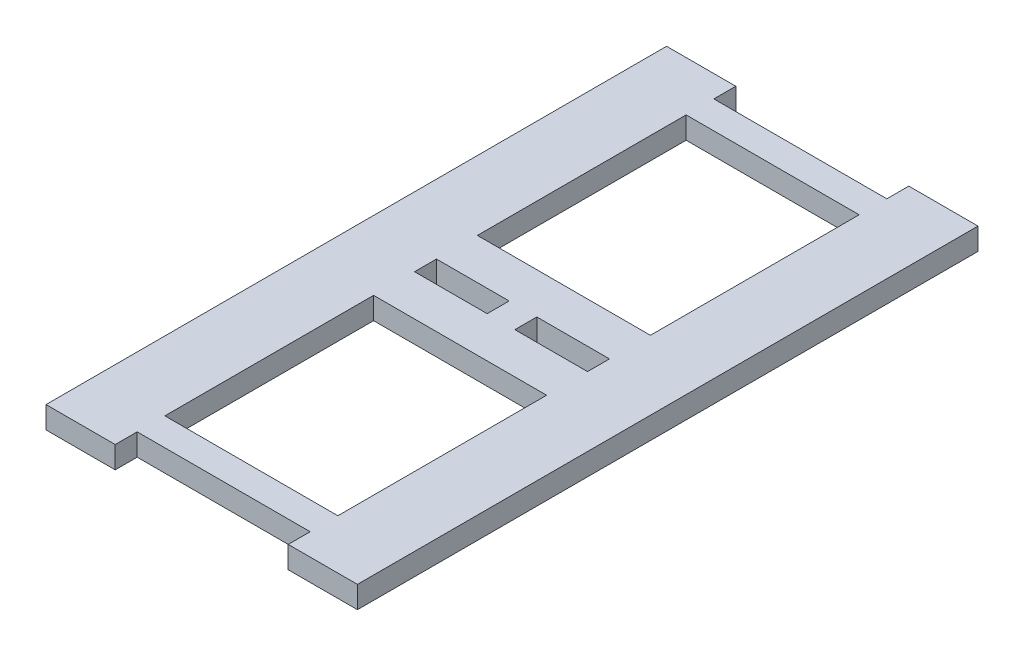
SolidWorks part; units mm, degrees
material "Mahogany"
ref_plane "Front Plane" through (0, 0, 0) normal (0, 0, 1) x (1, 0, 0)
ref_plane "Top Plane" through (0, 0, 0) normal (0, 1, 0) x (1, 0, 0)
ref_plane "Right Plane" through (0, 0, 0) normal (1, 0, 0) x (0, 0, -1)
sketch "Sketch1" plane through (0, 0, 0) normal (0, 0, 1) x (1, 0, 0)
  line L0 (-27.5, 19.2) -> (-27.5, 22.375) construction
  line L1 (-17.5, 22.375) -> (-17.5, 19.2) construction
  line L2 (-17.5, 19.2) -> (-27.5, 19.2) construction
  line L3 (-27.5, 22.375) -> (-17.5, 22.375) construction
  line L4 (-52.5, 22.375) -> (-52.5, 19.2) construction
  line L5 (-52.5, 19.2) -> (-62.5, 19.2) construction
  line L6 (-62.5, 22.375) -> (-52.5, 22.375) construction
  line L7 (-62.5, 19.2) -> (-62.5, 22.375) construction
  line L8 (-17.5, 19.2) -> (-27.5, 19.2)
  line L9 (-17.5, 22.375) -> (-17.5, 19.2)
  line L10 (-27.5, 22.375) -> (-17.5, 22.375)
  line L11 (-27.5, 19.2) -> (-27.5, 22.375)
  line L12 (-62.5, 19.2) -> (-62.5, 22.375)
  line L13 (-62.5, 22.375) -> (-52.5, 22.375)
  line L14 (-52.5, 22.375) -> (-52.5, 19.2)
  line L15 (-52.5, 19.2) -> (-62.5, 19.2)
extrude "Boss-Extrude1" add sketch "Sketch1" against normal up to surface (89.675 mm away)
sketch "Sketch2" plane through (0, 22.375, 0) normal (0, 1, 0) x (1, 0, 0)
  line L0 (-27.5, 86.5) -> (-52.5, 86.5)
  line L1 (-52.5, 86.5) -> (-52.5, 82.5)
  line L2 (-52.5, 89.675) -> (-52.5, 0) construction
  line L3 (-52.5, 82.5) -> (-27.5, 82.5)
  line L4 (-27.5, 89.675) -> (-27.5, 0) construction
  line L5 (-27.5, 82.5) -> (-27.5, 86.5)
  line L6 (-17.5, 44.8375) -> (-62.5, 44.8375) construction
  line L7 (-17.5, 89.675) -> (-17.5, 0) construction
  line L8 (-62.5, 89.675) -> (-62.5, 0) construction
  line L9 (-27.5, 7.175) -> (-27.5, 3.175)
  line L10 (-52.5, 7.175) -> (-27.5, 7.175)
  line L11 (-52.5, 3.175) -> (-52.5, 7.175)
  line L12 (-27.5, 3.175) -> (-52.5, 3.175)
  line L14 (-52.5, 37.3375) -> (-27.5, 37.3375)
  line L15 (-52.5, 37.3375) -> (-52.5, 52.3375)
  line L16 (-52.5, 52.3375) -> (-27.5, 52.3375)
  line L17 (-27.5, 37.3375) -> (-27.5, 52.3375)
  line L18 (-52.5, 37.3375) -> (-27.5, 52.3375) construction
  line L19 (-52.5, 52.3375) -> (-27.5, 37.3375) construction
  point P13 (-52.5, 44.8375)
  point P21 (-40, 44.8375)
  dimension "D1" = 4
  dimension "D2" = 15
extrude "Boss-Extrude2" add sketch "Sketch2" against normal up to surface (3.175 mm away) up to face at (-57.5, 19.2, -44.8375)
sketch "Sketch3" plane through (0, 22.375, 0) normal (0, 1, 0) x (1, 0, 0)
  line L0 (-17.5, 44.8375) -> (-62.5, 44.8375) construction
  line L1 (-40, 52.3375) -> (-40, 37.3375) construction
  line L2 (-52.5, 37.3375) -> (-52.5, 7.175) construction
  line L3 (-27.5, 7.175) -> (-52.5, 7.175) construction
  line L4 (-27.5, 37.3375) -> (-27.5, 7.175) construction
  line L5 (-52.5, 37.3375) -> (-27.5, 37.3375) construction
  line L6 (-27.5, 52.3375) -> (-52.5, 52.3375) construction
  line L7 (-52.5, 82.5) -> (-52.5, 52.3375) construction
  line L8 (-52.5, 82.5) -> (-27.5, 82.5) construction
  line L9 (-27.5, 82.5) -> (-27.5, 52.3375) construction
  line L10 (-52.5, 37.3375) -> (-52.5, 7.175) construction
  line L11 (-27.5, 7.175) -> (-52.5, 7.175) construction
  line L12 (-27.5, 37.3375) -> (-27.5, 7.175) construction
  line L13 (-52.5, 37.3375) -> (-27.5, 37.3375) construction
  line L14 (-17.5, 89.675) -> (-27.5, 89.675)
  line L15 (-27.5, 89.675) -> (-27.5, 86.5)
  line L16 (-27.5, 86.5) -> (-52.5, 86.5)
  line L17 (-52.5, 86.5) -> (-52.5, 89.675)
  line L18 (-52.5, 89.675) -> (-62.5, 89.675)
  line L19 (-62.5, 89.675) -> (-62.5, 0)
  line L20 (-62.5, 0) -> (-52.5, 0)
  line L21 (-52.5, 0) -> (-52.5, 3.175)
  line L22 (-52.5, 3.175) -> (-27.5, 3.175)
  line L23 (-27.5, 3.175) -> (-27.5, 0)
  line L24 (-27.5, 0) -> (-17.5, 0)
  line L25 (-17.5, 0) -> (-17.5, 89.675)
  line L26 (-17.5, 89.675) -> (-27.5, 89.675) construction
  line L27 (-27.5, 89.675) -> (-27.5, 86.5) construction
  line L28 (-27.5, 86.5) -> (-52.5, 86.5) construction
  line L29 (-52.5, 86.5) -> (-52.5, 89.675) construction
  line L30 (-52.5, 89.675) -> (-62.5, 89.675) construction
  line L31 (-62.5, 89.675) -> (-62.5, 0) construction
  line L32 (-62.5, 0) -> (-52.5, 0) construction
  line L33 (-52.5, 0) -> (-52.5, 3.175) construction
  line L34 (-52.5, 3.175) -> (-27.5, 3.175) construction
  line L35 (-27.5, 3.175) -> (-27.5, 0) construction
  line L36 (-27.5, 0) -> (-17.5, 0) construction
  line L37 (-17.5, 0) -> (-17.5, 89.675) construction
  line L38 (-27.5, 52.3375) -> (-52.5, 52.3375) construction
  line L39 (-52.5, 82.5) -> (-52.5, 52.3375) construction
  line L40 (-52.5, 82.5) -> (-27.5, 82.5) construction
  line L41 (-27.5, 82.5) -> (-27.5, 52.3375) construction
  line L42 (-42, 43.25) -> (-52.5, 46.425) construction
  line L52 (-27.5, 37.3375) -> (-52.5, 37.3375) construction
  line L64 (-38, 46.425) -> (-27.5, 46.425)
  line L65 (-38, 46.425) -> (-38, 43.25)
  line L66 (-38, 43.25) -> (-27.5, 43.25)
  line L67 (-27.5, 46.425) -> (-27.5, 43.25)
  line L68 (-38, 46.425) -> (-27.5, 43.25) construction
  line L69 (-38, 43.25) -> (-27.5, 46.425) construction
  line L70 (-42, 46.425) -> (-52.5, 43.25) construction
  line L71 (-52.5, 46.425) -> (-52.5, 43.25)
  line L72 (-42, 43.25) -> (-52.5, 43.25)
  line L73 (-42, 46.425) -> (-42, 43.25)
  line L74 (-42, 46.425) -> (-52.5, 46.425)
  point P12 (-32.75, 44.8375)
  point P33 (-47.25, 44.8375)
  dimension "D2" = 4
  dimension "D3" = 3.175
  dimension "D1" = 0
extrude "Cut-Extrude3" cut sketch "Sketch3" against normal up to surface (3.175 mm away) up to face at (-40, 19.2, -67.4188)
equation "\"prop-dist-width\"= 86.5mm"
equation "\"prop-dist-length\"= 80mm"
equation "\"prop-hole-diameter\"= 11mm"
equation "\"prop-boost\"= 4.4mm"
equation "\"back-drop\"= 5mm"
equation "\"T\"= 0.125in'Material Thickness"
equation "\"tof_c2c\"= 19.9mm'Center to center distance of TOF sensor holes"
equation "\"tof_d\"= 3mm'TOF hole diameter"
equation "\"tof_w\"= 12.6mm'TOF width"
equation "\"tof_l\"= 15.6mm'TOF length"
equation "\"pin_w\"= 2.3mm'A standard IO Pin socket width"
equation "\"pin_l\"= 2.5mm'A standard IO Pin socket length"
equation "\"esp_pin_num\"= 8'Number of pins on one side of the ESP"
equation "\"esp_l\"= 40mm'ESP length"
equation "\"esp_w\"= 27mm'ESP width"
equation "\"esp_pin_inset\"= 3mm'Distance that ESP pins are inset"
equation "\"bat_l\"= 27mm'Battery length"
equation "\"bat_w\"= 20mm'Battery width"
equation "\"bat_h\"= 6mm'Battery thickness"
equation "\"boost_w\"= 17.2mm"
equation "\"boost_l\"= 37mm"
equation "\"boost_hole_inset\"= 2.2mm"
equation "\"boost_hole_dist\"= 7mm"
equation "\"boost_hole_d\"= 2mm"
equation "\"prop-dist\"= 80mm"
equation "\"prop-hole-depth\"= 9mm"
equation "\"rivet-extension\"= 12mm"
equation "\"rivet-hole-extension\"= 7mm"
equation "\"rivet-hole-diameter\"= 3.8mm"
equation "\"ski-length\"= 100mm"
equation "\"th\"= 0.125in'material thickness"
equation "\"ski-height\"= 30mm"
equation "\"ski-curve-gap\"= 60mm"
equation "\"ski-curve-height\"= \"rivet-hole-extension\""
equation "\"min-width\"= 4mm"
equation "\"prop-hole-diameter-small\"= 8.6mm"
equation "\"support_width\"= 10mm"
equation "\"support_gap\"= 25mm"
equation "\"support_height\"= 21.5mm"
equation "\"D3@Sketch3\"=\"T\""
